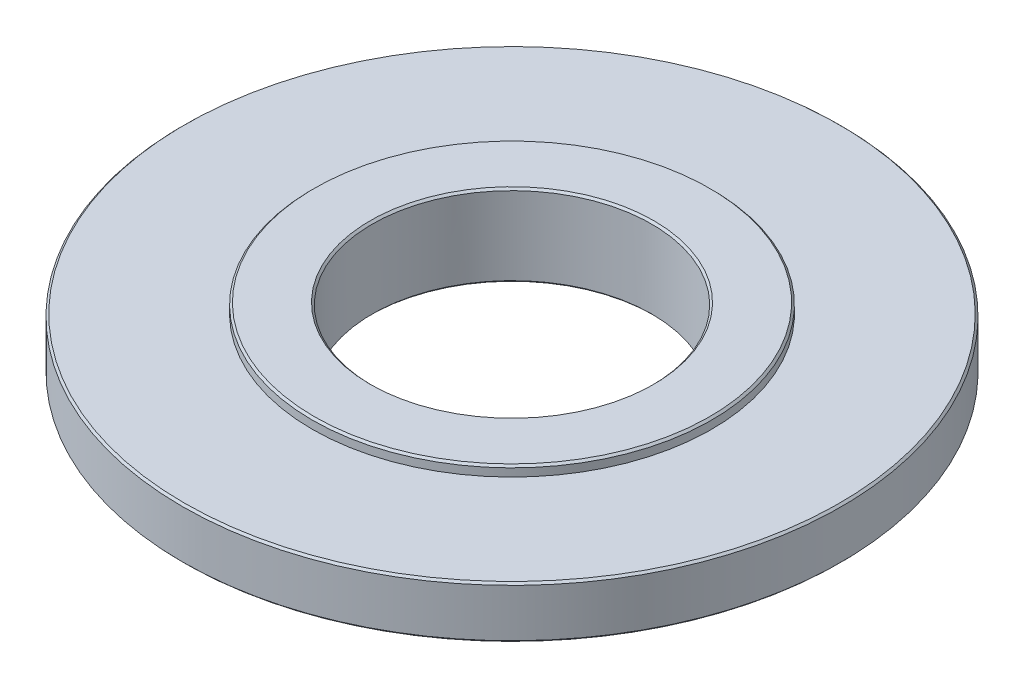
SolidWorks part; units mm, degrees
ref_plane "前基準面" through (0, 0, 0) normal (0, 0, 1) x (1, 0, 0)
ref_plane "上基準面" through (0, 0, 0) normal (0, 1, 0) x (1, 0, 0)
ref_plane "右基準面" through (0, 0, 0) normal (1, 0, 0) x (0, 0, -1)
ref_plane "平面1" through (0, 0, 0) normal (0, 0, -1) x (-1, 0, 0)
sketch "草圖1" plane through (0, 0, 0) normal (0, 0, -1) x (-1, 0, 0)
  line L0 (-82.5, 7) -> (0, 7)
  line L1 (0, 7) -> (0, 20)
  line L2 (0, 20) -> (-82.5, 20)
  line L3 (-82.5, 20) -> (-82.5, 7)
  line L4 (0, 7) -> (0, 20) construction
revolve "旋轉1" add sketch "草圖1" angle 360 about L4
sketch "草圖2" plane through (0, 7, 0) normal (0, -1, 0) x (1, 0, 0)
  circle A0 centre (0, 0) radius 70
extrude "填料-伸長1" add sketch "草圖2" along normal blind 5
sketch "草圖3" plane through (0, 20, 0) normal (0, 1, 0) x (-1, 0, 0)
  circle A0 centre (0, 0) radius 50
extrude "填料-伸長2" add sketch "草圖3" along normal blind 2.5
hole_wizard "鑽孔2" positions "草圖7" profile "草圖6" legacy
sketch "草圖7" plane through (0, 22.5, 0) normal (0, 1, 0) x (1, 0, 0)
  point P0 (0, 0)
sketch "草圖6" plane through (0, 22.5, 0) normal (1, 0, 0) x (0, 0, 1)
  line L0 (0, 0) -> (0, 20.5)
  line L1 (0, 20.5) -> (35, 20.5)
  line L2 (35, 20.5) -> (35, 0)
  line L3 (35, 0) -> (0, 0)
  line L4 (0, 110) -> (0, -10) construction
  dimension "直徑" = 70
  dimension "深度" = 20.5
chamfer "導角1" distance 0.5 angle 45 6 edges at (0, 7, 82.5) (0, 20, 82.5) (0, 22.5, 50) (0, 2, -70) (0, 2, 35) (0, 22.5, 35)
